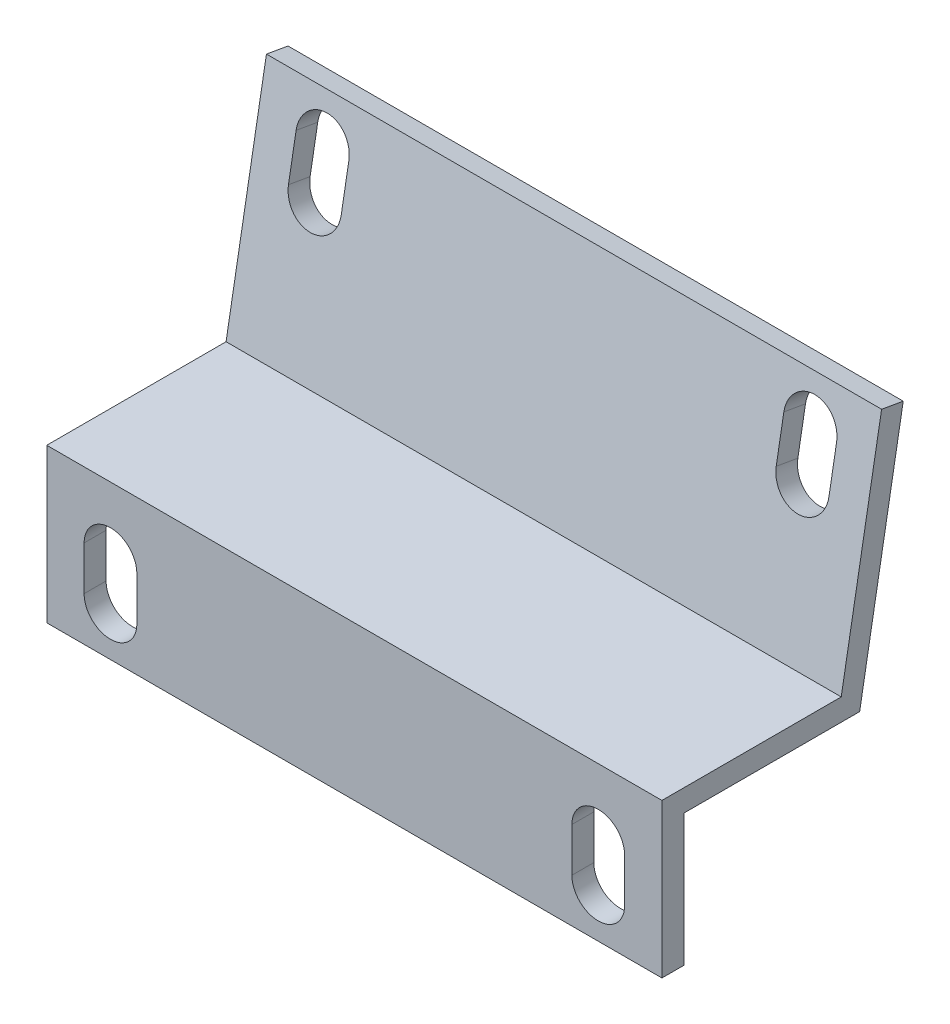
SolidWorks part; units mm, degrees
ref_plane "前视基准面" through (0, 0, 0) normal (0, 0, 1) x (1, 0, 0)
ref_plane "上视基准面" through (0, 0, 0) normal (0, 1, 0) x (1, 0, 0)
ref_plane "右视基准面" through (0, 0, 0) normal (1, 0, 0) x (0, 0, -1)
other "Configuration Table"
sketch "草图1" plane through (0, 0, 0) normal (1, 0, 0) x (0, 0, -1)
  line L0 (0, 0) -> (20, 0)
  line L1 (20, 0) -> (24.9575, 28.1152)
  line L2 (0, 0) -> (0, -15)
  line L3 (-2.5, 2.5) -> (-2.5, -15)
  line L4 (-2.5, 2.5) -> (17.9023, 2.5)
  line L5 (17.9023, 2.5) -> (22.4954, 28.5493)
  line L6 (-2.5, -15) -> (0, -15)
  line L8 (22.4954, 28.5493) -> (24.9575, 28.1152)
  line L9 (17.9023, 2.5) -> (27.0886, 54.5985) construction
  line L10 (20, 0) -> (29.5506, 54.1644) construction
  dimension "D1" = 2.5
extrude "凸台-拉伸1" add sketch "草图1" along normal blind 70
sketch "草图2" plane through (0, 0, 2.5) normal (0, 0, 1) x (1, 0, 0)
  line L0 (7.25, -10) -> (7.25, -5) construction
  line L1 (4.25, -10) -> (4.25, -5)
  line L2 (10.25, -10) -> (10.25, -5)
  line L6 (62.75, -10) -> (62.75, -5) construction
  line L7 (65.75, -10) -> (65.75, -5)
  line L8 (59.75, -10) -> (59.75, -5)
  arc A0 (4.25, -10) -> (10.25, -10) centre (7.25, -10) ccw
  arc A1 (10.25, -5) -> (4.25, -5) centre (7.25, -5) ccw
  arc A2 (65.75, -10) -> (59.75, -10) centre (62.75, -10) cw
  arc A3 (59.75, -5) -> (65.75, -5) centre (62.75, -5) cw
  point P2 (7.25, -7.5)
  point P16 (62.75, -7.5)
extrude "切除-拉伸1" cut sketch "草图2" against normal blind 70
sketch "草图3" plane through (0, -2.9861, -16.9349) normal (0, 0.1736, 0.9848) x (1, 0, 0)
  line L0 (0, 32.0218) -> (0, 27.0218)
  line L1 (0, 32.0218) -> (0, 5.5707) construction
  line L5 (7.25, 26.9949) -> (7.25, 21.9949) construction
  line L6 (10.25, 26.9949) -> (10.25, 21.9949)
  line L7 (4.25, 26.9949) -> (4.25, 21.9949)
  line L8 (62.75, 26.9949) -> (62.75, 21.9949) construction
  line L12 (65.75, 26.9949) -> (65.75, 21.9949)
  line L13 (59.75, 26.9949) -> (59.75, 21.9949)
  arc A4 (10.25, 26.9949) -> (4.25, 26.9949) centre (7.25, 26.9949) ccw
  arc A5 (4.25, 21.9949) -> (10.25, 21.9949) centre (7.25, 21.9949) ccw
  arc A6 (65.75, 26.9949) -> (59.75, 26.9949) centre (62.75, 26.9949) ccw
  arc A7 (59.75, 21.9949) -> (65.75, 21.9949) centre (62.75, 21.9949) ccw
  point P13 (7.25, 24.4949)
  point P28 (62.75, 24.4949)
extrude "切除-拉伸2" cut sketch "草图3" against normal blind 10 contours L7 A5 L6 A4 | L13 A7 L12 A6
